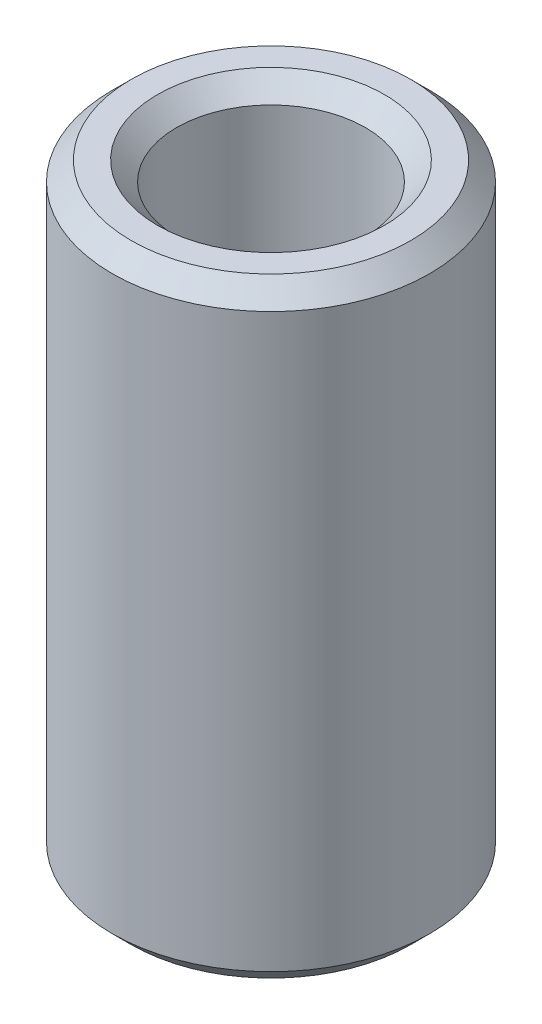
SolidWorks part; units mm, degrees
material "ABS"
ref_plane "Alzado" through (0, 0, 0) normal (0, 0, 1) x (1, 0, 0)
ref_plane "Planta" through (0, 0, 0) normal (0, 1, 0) x (1, 0, 0)
ref_plane "Vista lateral" through (0, 0, 0) normal (1, 0, 0) x (0, 0, -1)
sketch "Croquis1" plane through (0, 0, 0) normal (0, 1, 0) x (1, 0, 0)
  circle A0 centre (0, 0) radius 3.715
  circle A1 centre (0, 0) radius 6.25
  dimension "D1" = 7.43
  dimension "D2" = 12.5
extrude "Saliente-Extruir1" add sketch "Croquis1" along normal mid plane 24
chamfer "Chaflán1" distance 0.75 angle 45 4 edges at (0, 12, 3.715) (0, -12, 3.715) (0, -12, 6.25) (0, 12, 6.25)
